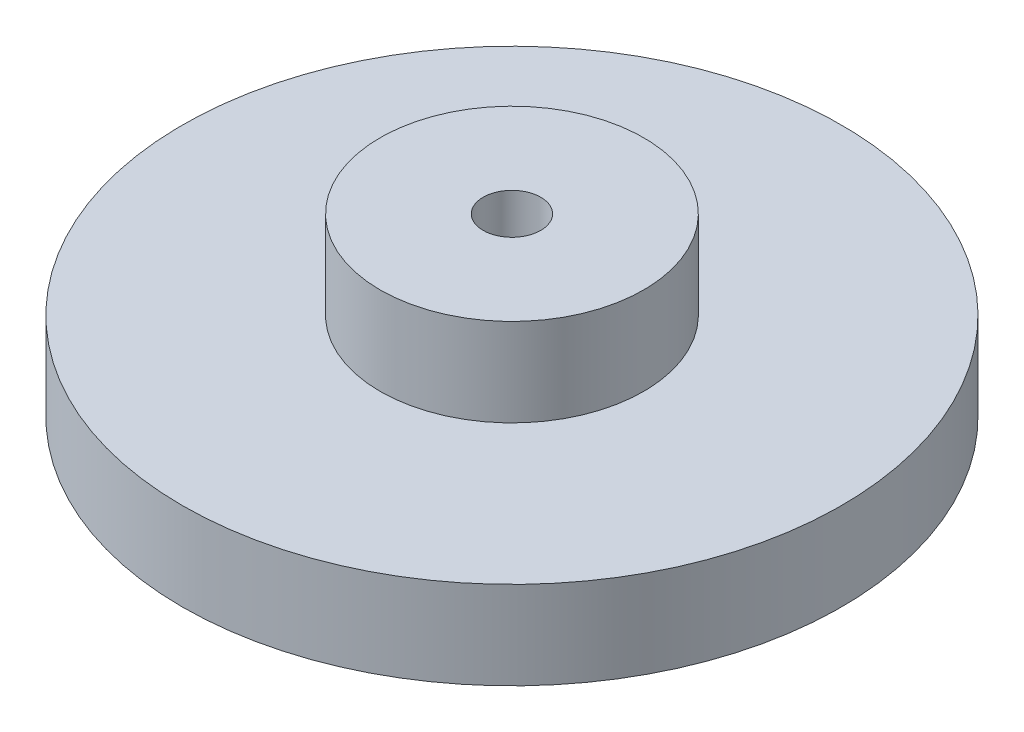
SolidWorks part; units mm, degrees
ref_plane "Front Plane" through (0, 0, 0) normal (0, 0, 1) x (1, 0, 0)
ref_plane "Top Plane" through (0, 0, 0) normal (0, 1, 0) x (1, 0, 0)
ref_plane "Right Plane" through (0, 0, 0) normal (1, 0, 0) x (0, 0, -1)
sketch "Sketch1" plane through (0, 0, 0) normal (0, 1, 0) x (1, 0, 0)
  circle A0 centre (0, 0) radius 7.5
  dimension "D1" = 15
extrude "Boss-Extrude1" add sketch "Sketch1" along normal blind 2
sketch "Sketch2" plane through (0, 2, 0) normal (0, 1, 0) x (1, 0, 0)
  circle A0 centre (0, 0) radius 3
  dimension "D1" = 6
extrude "Boss-Extrude2" add sketch "Sketch2" along normal blind 2
sketch "Sketch3" plane through (0, 4, 0) normal (0, 1, 0) x (1, 0, 0)
  circle A0 centre (0, 0) radius 0.655
  dimension "D1" = 1.31
extrude "Cut-Extrude1" cut sketch "Sketch3" against normal blind 2.89
sketch "Sketch4" plane through (0, 1.11, 0) normal (0, 1, 0) x (1, 0, 0)
  circle A0 centre (0, 0) radius 0.655
extrude "Cut-Extrude3" cut sketch "Sketch4" against normal blind 1.11 draft 60 draft outward yes
